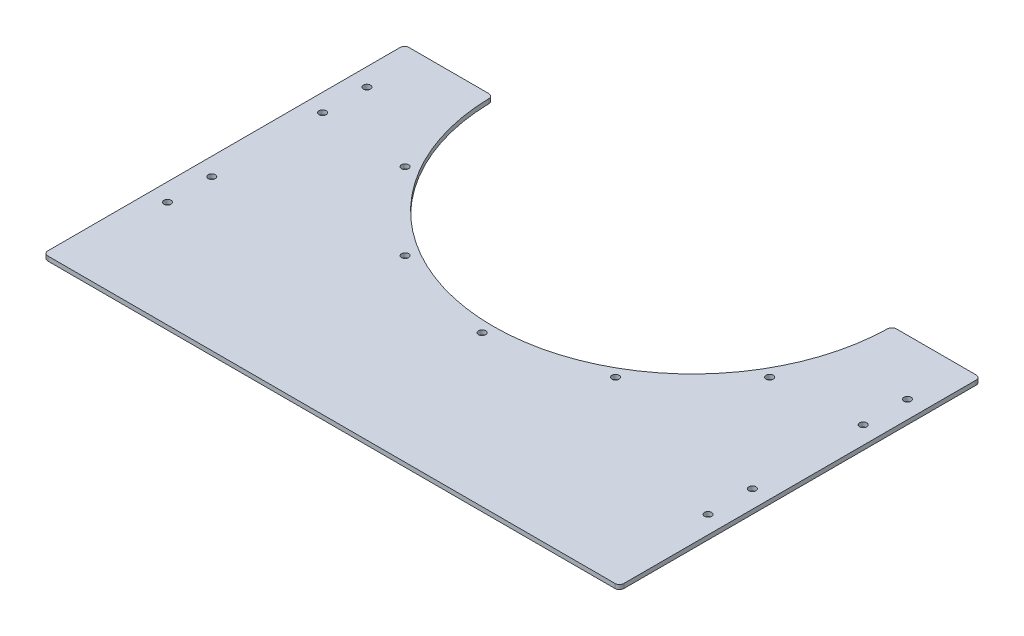
SolidWorks part; units mm, degrees
material "Thornel Mat VMA"
ref_plane "前视基准面" through (0, 0, 0) normal (0, 0, 1) x (1, 0, 0)
ref_plane "上视基准面" through (0, 0, 0) normal (0, 1, 0) x (1, 0, 0)
ref_plane "右视基准面" through (0, 0, 0) normal (1, 0, 0) x (0, 0, -1)
other "Configuration Table"
sketch "草图1" plane through (0, 0, 0) normal (0, 1, 0) x (1, 0, 0)
  line L0 (-122, 81.5) -> (-122, -81.5) construction
  line L1 (130, -81.5) -> (-130, -81.5)
  line L2 (130, -81.5) -> (130, 81.5)
  line L3 (130, 81.5) -> (-130, 81.5)
  line L4 (-130, -81.5) -> (-130, 81.5)
  line L5 (130, -81.5) -> (-130, 81.5) construction
  line L6 (130, 81.5) -> (-130, -81.5) construction
  line L7 (0, 81.5) -> (0, -81.5) construction
  circle A0 centre (0, 81.5) radius 90
  circle A1 centre (-122, -33.5) radius 1.6
  circle A2 centre (-122, -13.5) radius 1.6
  circle A3 centre (-122, 36.5) radius 1.6
  circle A4 centre (-122, 56.5) radius 1.6
  circle A5 centre (122, -33.5) radius 1.6
  circle A6 centre (122, -13.5) radius 1.6
  circle A7 centre (122, 36.5) radius 1.6
  circle A8 centre (122, 56.5) radius 1.6
  circle A9 centre (0, 81.5) radius 95 construction
  circle A14 centre (82.2724, 34) radius 1.6
  circle A15 centre (47.5, -0.7724) radius 1.6
  circle A16 centre (0, -13.5) radius 1.6
  circle A17 centre (-47.5, -0.7724) radius 1.6
  circle A18 centre (-82.2724, 34) radius 1.6
  point P0 (0, 0)
  dimension "D3" = 163
  dimension "D4" = 180
  dimension "D5" = 3.2
  dimension "D7" = 20
  dimension "D8" = 50
  dimension "D9" = 20
  dimension "D10" = 48
  dimension "D11" = 190
  dimension "D1" = 260
  dimension "D2" = 163
  dimension "D6" = 8
extrude "凸台-拉伸1" add sketch "草图1" along normal blind 2 contours A0 L3 L4 L1 L2 A7 A5 A4 A3 A2 A1 A6 A8
fillet "圆角1" radius 2 6 edges at (-90, 1, -81.5) (90, 1, -81.5) (130, 1, -81.5) (130, 1, 81.5) (-130, 1, 81.5) (-130, 1, -81.5)
